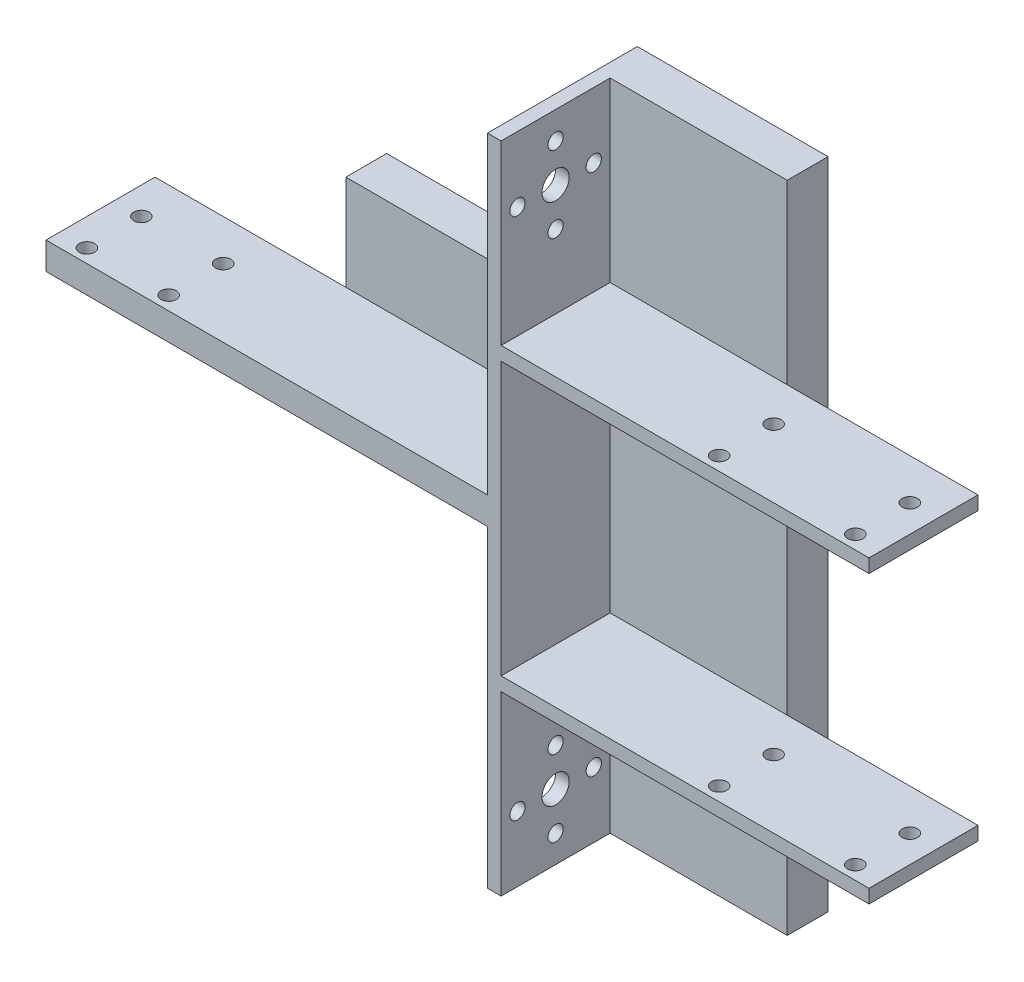
SolidWorks part; units mm, degrees
ref_plane "Front Plane" through (0, 0, 0) normal (0, 0, 1) x (1, 0, 0)
ref_plane "Top Plane" through (0, 0, 0) normal (0, 1, 0) x (1, 0, 0)
ref_plane "Right Plane" through (0, 0, 0) normal (1, 0, 0) x (0, 0, -1)
sketch "Sketch1" plane through (0, 0, 0) normal (0, 0, 1) x (1, 0, 0)
  line L1 (-35, 60) -> (0, 60)
  line L2 (-35, 60) -> (-35, -60)
  line L3 (-35, -60) -> (0, -60)
  line L4 (0, 60) -> (0, -60)
  line L5 (-35, 20) -> (-81, 20)
  line L6 (-35, 20) -> (-35, -20)
  line L7 (-35, -20) -> (-81, -20)
  line L8 (-81, 20) -> (-81, -20)
  point P4 (0, 0)
  point P11 (-81, 0)
  dimension "D1" = 35
  dimension "D2" = 120
  dimension "D3" = 46
  dimension "D4" = 40
extrude "Boss-Extrude2" add sketch "Sketch1" along normal blind 7.5 contours L5 L8 L7 L2 | L4 L1 L2 L3
sketch "Sketch2" plane through (0, 0, 7.5) normal (0, 0, 1) x (1, 0, 0)
  line L0 (-35, -60) -> (0, -60) construction
  line L1 (-35, 60) -> (-32.5, 60)
  line L2 (-35, 60) -> (-35, -60)
  line L3 (-35, -60) -> (-32.5, -60)
  line L4 (-32.5, 60) -> (-32.5, -60)
  line L5 (-81, 20) -> (-81, -20) construction
  line L6 (-35, -2.5) -> (-116, -2.5)
  line L7 (-35, -2.5) -> (-35, 2.5)
  line L8 (-35, 2.5) -> (-116, 2.5)
  line L9 (-116, -2.5) -> (-116, 2.5)
  line L10 (-32.5, 25) -> (35, 25)
  line L11 (-32.5, 25) -> (-32.5, 27.5)
  line L12 (-32.5, 27.5) -> (35, 27.5)
  line L13 (35, 25) -> (35, 27.5)
  line L14 (-32.5, -27.5) -> (35, -27.5)
  line L15 (-32.5, -27.5) -> (-32.5, -25)
  line L16 (-32.5, -25) -> (35, -25)
  line L17 (35, -27.5) -> (35, -25)
  line L18 (0, 60) -> (0, -60) construction
  line L19 (1.25, 25) -> (1.25, -25) construction
  point P19 (-116, 0)
  point P27 (1.25, 0)
  line M18 (-81, 20) -> (-81, -20)
  line M20 (-35, -20) -> (-35, -60)
  line M21 (-35, -60) -> (0, -60)
  line M22 (0, -60) -> (0, 60)
  line M23 (0, 60) -> (-35, 60)
  line M24 (-35, 60) -> (-35, 20)
  dimension "D1" = 35
  dimension "D2" = 5
  dimension "D3" = 2.5
  dimension "D4" = 2.5
  dimension "D5" = 35
  dimension "D6" = 50
extrude "Boss-Extrude3" add sketch "Sketch2" along normal blind 20 contours L2 L8 L6 M18 | L4 L2 M23 M24 M20 M21 | L12 L4 L10 M22 | L10 L13 L12 M22 | L14 L17 L16 M22 | L16 L4 L14 M22 | L9 L6 L8 M18
sketch "Sketch3" plane through (0, -27.5, 0) normal (0, -1, 0) x (1, 0, 0)
  line L0 (5, 25) -> (30, 25) construction
  line L1 (30, 25) -> (30, 15) construction
  line L2 (30, 15) -> (5, 15) construction
  line L3 (5, 15) -> (5, 25) construction
  line L5 (35, 27.5) -> (35, 7.5) construction
  line L6 (-32.5, 27.5) -> (35, 27.5) construction
  circle A0 centre (30, 25) radius 1.4
  circle A1 centre (30, 15) radius 1.4
  circle A2 centre (5, 25) radius 1.4
  circle A3 centre (5, 15) radius 1.4
  dimension "D1" = 2.8
  dimension "D2" = 25
  dimension "D3" = 10
  dimension "D4" = 5
  dimension "D5" = 2.5
extrude "Cut-Extrude1" cut sketch "Sketch3" against normal blind 60
sketch "Sketch4" plane through (0, -2.5, 0) normal (0, -1, 0) x (1, 0, 0)
  line L0 (-111, 25) -> (-96, 25) construction
  line L1 (-96, 25) -> (-96, 15) construction
  line L2 (-96, 15) -> (-111, 15) construction
  line L3 (-111, 15) -> (-111, 25) construction
  line L4 (-116, 27.5) -> (-116, 7.5) construction
  line L5 (-35, 27.5) -> (-116, 27.5) construction
  circle A0 centre (-111, 25) radius 1.4
  circle A1 centre (-96, 25) radius 1.4
  circle A2 centre (-96, 15) radius 1.4
  circle A3 centre (-111, 15) radius 1.4
  dimension "D1" = 2.8
  dimension "D2" = 15
  dimension "D3" = 10
  dimension "D4" = 5
  dimension "D5" = 2.5
extrude "Cut-Extrude2" cut sketch "Sketch4" against normal blind 6
sketch "Sketch6" plane through (-32.5, 0, 0) normal (1, 0, 0) x (0, 0, -1)
  line L0 (-24.5, -48) -> (-17.5, -48) construction
  line L1 (-17.5, -48) -> (-17.5, -55) construction
  line L4 (-27.5, -60) -> (-7.5, -60) construction
  line L5 (-27.5, -27.5) -> (-27.5, -60) construction
  line L6 (-43.6365, 0) -> (16.0902, 0) construction
  line L7 (-17.5, 48) -> (-17.5, 55) construction
  line L8 (-24.5, 48) -> (-17.5, 48) construction
  circle A0 centre (-24.5, -48) radius 1.4
  circle A1 centre (-17.5, -48) radius 2.5
  circle A2 centre (-17.5, -55) radius 1.4
  circle A3 centre (-17.5, -41) radius 1.4
  circle A4 centre (-10.5, -48) radius 1.4
  circle A5 centre (-10.5, 48) radius 1.4
  circle A6 centre (-17.5, 41) radius 1.4
  circle A7 centre (-17.5, 55) radius 1.4
  circle A8 centre (-17.5, 48) radius 2.5
  circle A9 centre (-24.5, 48) radius 1.4
  dimension "D1" = 2.8
  dimension "D2" = 5
  dimension "D3" = 12
  dimension "D4" = 10
  dimension "D5" = 7
extrude "Cut-Extrude3" cut sketch "Sketch6" against normal blind 2.5
